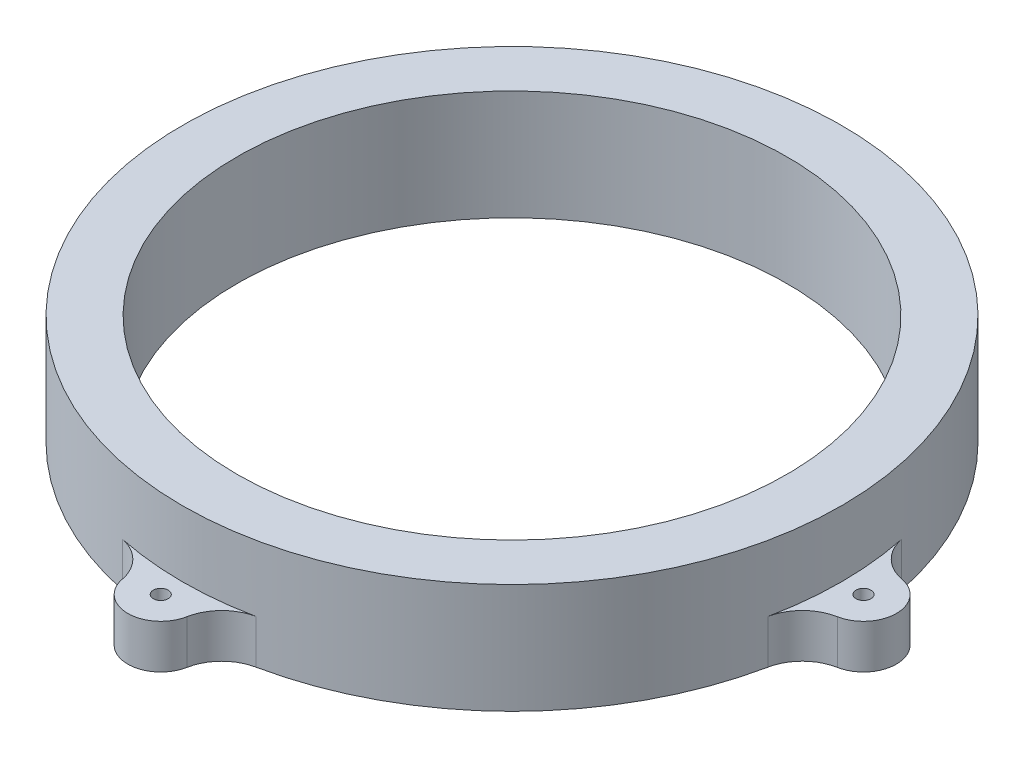
SolidWorks part; units mm, degrees
ref_plane "Front Plane" through (0, 0, 0) normal (0, 0, 1) x (1, 0, 0)
ref_plane "Top Plane" through (0, 0, 0) normal (0, 1, 0) x (1, 0, 0)
ref_plane "Right Plane" through (0, 0, 0) normal (1, 0, 0) x (0, 0, -1)
sketch "Sketch1" plane through (0, 0, 0) normal (0, 1, 0) x (1, 0, 0)
  line L0 (0, 0) -> (0, 80) construction
  line L1 (-7.5, 80) -> (-7.5, 74.6241)
  line L2 (7.5, 80) -> (7.5, 74.6241)
  line L3 (79.9758, 7.5242) -> (74.6216, 7.5242)
  line L4 (79.9758, -7.4758) -> (74.6265, -7.4758)
  line L5 (7.5, -79.9516) -> (7.0048, -74.6722)
  line L6 (-7.5, -79.9516) -> (-7.5, -74.6241)
  line L7 (-79.9758, 7.5242) -> (-74.6216, 7.5242)
  line L8 (-79.9758, -7.4758) -> (-74.6265, -7.4758)
  circle A0 centre (0, 0) radius 62.6
  circle A1 centre (0, 0) radius 75
  circle A2 centre (0, 80) radius 1.7
  circle A3 centre (0, 80) radius 7.5
  circle A4 centre (79.9758, 0.0242) radius 7.5
  circle A5 centre (79.9758, 0.0242) radius 1.7
  circle A6 centre (0, -79.9516) radius 7.5
  circle A7 centre (0, -79.9516) radius 1.7
  circle A8 centre (-79.9758, 0.0242) radius 7.5
  circle A9 centre (-79.9758, 0.0242) radius 1.7
  arc A10 (-37.9543, 64.6875) -> (37.9543, 64.6875) centre (0, 0) cw
  arc A11 (64.6875, 37.9543) -> (64.6875, -37.9543) centre (0, 0) cw
  arc A12 (37.9543, -64.6875) -> (-37.9543, -64.6875) centre (0, 0) cw
  arc A13 (-64.6875, -37.9543) -> (-64.6875, 37.9543) centre (0, 0) cw
  point P35 (0, 0.0242)
  dimension "D1" = 125.2
  dimension "D2" = 150
  dimension "D4" = 3.4
  dimension "D5" = 15
  dimension "D3" = 80
  dimension "D6" = 4
extrude "Boss-Extrude1" add sketch "Sketch1" along normal blind 10 contours A1 | A0 | A3 | A2 | A4 | A5 | A6 | A7 | A8 | A9
fillet "Fillet1" radius 10 8 edges at (-74.8015, 5, -5.4534) (-74.8048, 5, 5.4081) (-5.4522, 5, 74.8016) (5.4522, 5, 74.8016) (74.8048, 5, 5.4081) (74.8015, 5, -5.4534) (5.4091, 5, -74.8047) (-5.4091, 5, -74.8047)
sketch "Sketch2" plane through (0, 10, 0) normal (0, 1, 0) x (1, 0, 0)
  circle A0 centre (0, 0) radius 62.6
  circle A1 centre (0, 0) radius 75
extrude "Boss-Extrude2" add sketch "Sketch2" along normal blind 15
